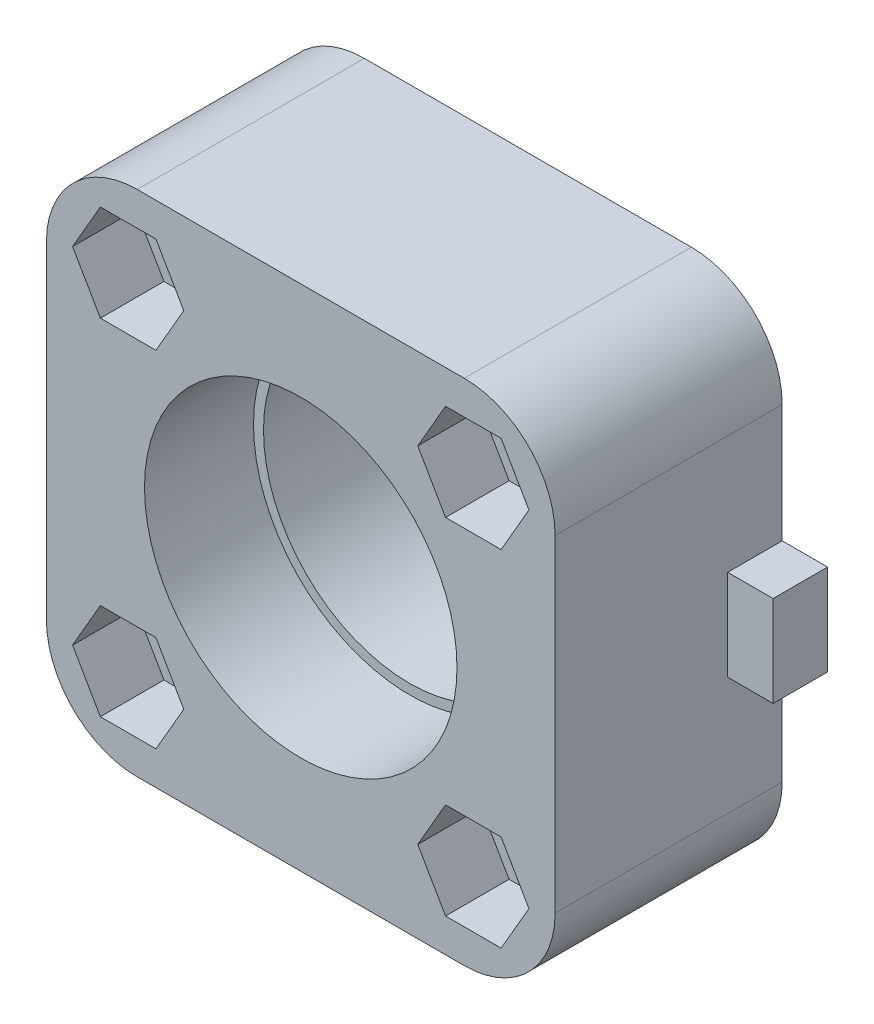
SolidWorks part; units mm, degrees
ref_plane "Alzado" through (0, 0, 0) normal (0, 0, 1) x (1, 0, 0)
ref_plane "Planta" through (0, 0, 0) normal (0, 1, 0) x (1, 0, 0)
ref_plane "Vista lateral" through (0, 0, 0) normal (1, 0, 0) x (0, 0, -1)
sketch "Croquis1" plane through (0, 0, 0) normal (0, 0, 1) x (1, 0, 0)
  line L1 (-14, -14) -> (14, -14)
  line L2 (-14, -14) -> (-14, 14)
  line L3 (-14, 14) -> (14, 14)
  line L4 (14, -14) -> (14, 14)
  line L5 (-14, -14) -> (14, 14) construction
  line L6 (-14, 14) -> (14, -14) construction
  circle A0 centre (0, 0) radius 8.05
  dimension "D1" = 16.1
  dimension "D2" = 28
  dimension "D3" = 28
extrude "Saliente-Extruir1" add sketch "Croquis1" along normal mid plane 6.5
sketch "Croquis2" plane through (0, 0, 3.25) normal (0, 0, 1) x (1, 0, 0)
  line L4 (14, -14) -> (14, 14)
  line L5 (14, 14) -> (-14, 14)
  line L6 (-14, 14) -> (-14, -14)
  line L7 (-14, -14) -> (14, -14)
  line L8 (14, -14) -> (14, 14)
  line L9 (14, 14) -> (-14, 14)
  line L10 (-14, 14) -> (-14, -14)
  line L11 (-14, -14) -> (14, -14)
  circle A0 centre (0, 0) radius 8.6
  dimension "D2" = 17.2
  dimension "D1" = 0
extrude "Saliente-Extruir2" add sketch "Croquis2" along normal blind 6
sketch "Croquis3" plane through (0, 0, 9.25) normal (0, 0, 1) x (1, 0, 0)
  line L0 (-9.5, 9.5) -> (9.5, 9.5) construction
  line L1 (9.5, 9.5) -> (9.5, -9.5) construction
  line L2 (9.5, -9.5) -> (-9.5, -9.5) construction
  line L3 (-9.5, -9.5) -> (-9.5, 9.5) construction
  line L5 (0, 13.0603) -> (0, -13.8489) construction
  line L6 (15.5492, 0) -> (-17.9148, 0) construction
  line L7 (11.03, 12.15) -> (7.97, 12.15)
  line L8 (-6.44, 9.5) -> (-7.97, 12.15)
  line L9 (-7.97, 12.15) -> (-11.03, 12.15)
  line L10 (-11.03, 12.15) -> (-12.56, 9.5)
  line L11 (-12.56, 9.5) -> (-11.03, 6.85)
  line L12 (-11.03, 6.85) -> (-7.97, 6.85)
  line L13 (-7.97, 6.85) -> (-6.44, 9.5)
  line L14 (7.97, 12.15) -> (6.44, 9.5)
  line L15 (6.44, 9.5) -> (7.97, 6.85)
  line L16 (7.97, 6.85) -> (11.03, 6.85)
  line L17 (11.03, 6.85) -> (12.56, 9.5)
  line L18 (12.56, 9.5) -> (11.03, 12.15)
  line L19 (-7.97, -6.85) -> (-11.03, -6.85)
  line L20 (-11.03, -6.85) -> (-12.56, -9.5)
  line L21 (-12.56, -9.5) -> (-11.03, -12.15)
  line L22 (-11.03, -12.15) -> (-7.97, -12.15)
  line L23 (-7.97, -12.15) -> (-6.44, -9.5)
  line L24 (-6.44, -9.5) -> (-7.97, -6.85)
  line L25 (11.03, -6.85) -> (7.97, -6.85)
  line L26 (7.97, -6.85) -> (6.44, -9.5)
  line L27 (6.44, -9.5) -> (7.97, -12.15)
  line L28 (7.97, -12.15) -> (11.03, -12.15)
  line L29 (11.03, -12.15) -> (12.56, -9.5)
  line L30 (12.56, -9.5) -> (11.03, -6.85)
  circle A0 centre (-9.5, 9.5) radius 1.5 construction
  circle A1 centre (-9.5, -9.5) radius 1.5 construction
  circle A2 centre (9.5, -9.5) radius 1.5 construction
  circle A3 centre (9.5, 9.5) radius 1.5 construction
  circle A4 centre (-9.5, 9.5) radius 2.65 construction
  circle A5 centre (9.5, 9.5) radius 2.65 construction
  circle A6 centre (-9.5, -9.5) radius 2.65 construction
  circle A7 centre (9.5, -9.5) radius 2.65 construction
  point P13 (0, -9.5)
  point P14 (-9.5, 0)
  dimension "D1" = 3
  dimension "D2" = 19
  dimension "D3" = 19
  dimension "D4" = 5.3
extrude "Cortar-Extruir1" cut sketch "Croquis3" against normal blind 3.5
sketch "Croquis6" plane through (0, 0, -3.25) normal (0, 0, -1) x (-1, 0, 0)
  line L0 (-9.5, 9.5) -> (9.5, 9.5) construction
  line L1 (9.5, 9.5) -> (9.5, -9.5) construction
  line L2 (9.5, -9.5) -> (-9.5, -9.5) construction
  line L3 (-9.5, -9.5) -> (-9.5, 9.5) construction
  line L4 (0, 17.9373) -> (0, -16.6332) construction
  line L5 (16.9599, 0) -> (-18.6245, 0) construction
  circle A0 centre (-9.5, 9.5) radius 1.5
  circle A1 centre (9.5, 9.5) radius 1.5
  circle A2 centre (9.5, -9.5) radius 1.5
  circle A3 centre (-9.5, -9.5) radius 1.5
  point P13 (0, 9.5)
  point P14 (-9.5, 0)
  dimension "D1" = 3
  dimension "D2" = 19
  dimension "D3" = 19
extrude "Cortar-Extruir2" cut sketch "Croquis6" against normal blind 23.5
sketch "Croquis7" plane through (0, 0, -3.25) normal (0, 0, -1) x (-1, 0, 0)
  line L0 (14, -14) -> (-14, -14) construction
  line L1 (-5, -14) -> (5, -14)
  line L2 (-5, -14) -> (-5, -18)
  line L3 (-5, -18) -> (5, -18)
  line L4 (5, -14) -> (5, -18)
  line L5 (-14, -14) -> (-14, 14) construction
  line L6 (-14, 2.5) -> (-16.5, 2.5)
  line L7 (-14, 2.5) -> (-14, -2.5)
  line L8 (-14, -2.5) -> (-16.5, -2.5)
  line L9 (-16.5, 2.5) -> (-16.5, -2.5)
  line L10 (14, 14) -> (14, -14) construction
  line L11 (14, 2.5) -> (16.5, 2.5)
  line L12 (14, 2.5) -> (14, -2.5)
  line L13 (14, -2.5) -> (16.5, -2.5)
  line L14 (16.5, 2.5) -> (16.5, -2.5)
  line L15 (0, 20.1506) -> (0, -30.1017) construction
  line L16 (-29.8997, 0) -> (35.1473, 0) construction
  line L17 (14, 5.5) -> (18.9, 5.5)
  line L18 (14, -2.5) -> (18.9, -2.5)
  line L19 (14, -2.5) -> (14, -5.5)
  line L20 (14, -5.5) -> (18.9, -5.5)
  line L21 (18.9, -2.5) -> (18.9, -5.5)
  line L22 (18.9, 2.5) -> (18.9, 5.5)
  line L23 (14, 2.5) -> (18.9, 2.5)
  line L24 (14, 2.5) -> (14, 5.5)
  point P23 (-16.5, 0)
  point P24 (16.5, 0)
  point P25 (0, -18)
  line M19 (-14, 14) -> (-14, -14)
  line M20 (-14, -14) -> (14, -14)
  line M21 (14, -14) -> (14, 14)
  dimension "D1" = 10
  dimension "D2" = 4
  dimension "D3" = 2.5
  dimension "D4" = 5
  dimension "D5" = 5
  dimension "D6" = 2.5
  dimension "D7" = 4.9
  dimension "D8" = 3
extrude "Saliente-Extruir3" add sketch "Croquis7" against normal blind 3 contours L11 L23 L22 L17 M21 | L14 L11 L13 M21 | L21 L18 L13 L20 M21 | L4 L2 L3 M20 | L6 L9 L8 M19
fillet "Redondeo1" radius 5 4 edges at (-14, 14, 3) (-14, -14, 3) (14, -14, 3) (14, 14, 3)
